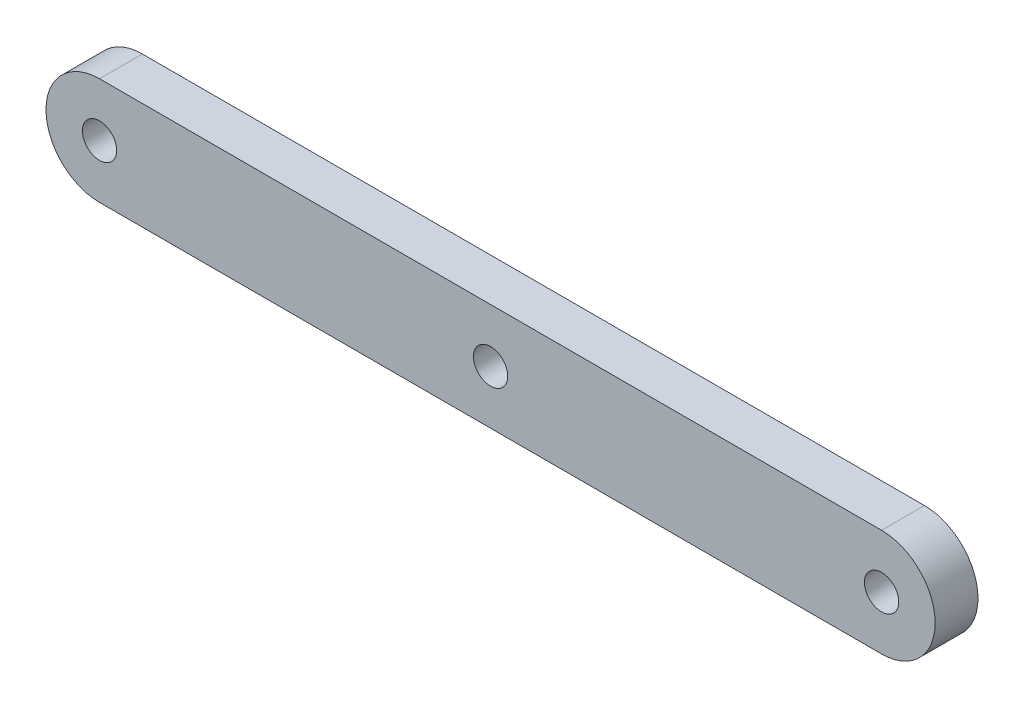
SolidWorks part; units mm, degrees
ref_plane "前视基准面" through (0, 0, 0) normal (0, 0, 1) x (1, 0, 0)
ref_plane "上视基准面" through (0, 0, 0) normal (0, 1, 0) x (1, 0, 0)
ref_plane "右视基准面" through (0, 0, 0) normal (1, 0, 0) x (0, 0, -1)
other "Configuration Table"
sketch "草图2" plane through (0, 0, 0) normal (0, 0, 1) x (1, 0, 0)
  line L0 (-43.2134, 33.7207) -> (-43.2134, 23.7207) construction
  line L1 (-79.7134, 33.7207) -> (-6.7134, 33.7207)
  line L3 (-79.7134, 23.7207) -> (-6.7134, 23.7207)
  line L6 (-37.9142, 23.7207) -> (-6.7134, 33.7207) construction
  arc A0 (-79.7134, 33.7207) -> (-79.7134, 23.7207) centre (-79.7134, 28.7207) ccw
  arc A1 (-6.7134, 33.7207) -> (-6.7134, 23.7207) centre (-6.7134, 28.7207) cw
  circle A2 centre (-79.7134, 28.7207) radius 1.6
  circle A3 centre (-6.7134, 28.7207) radius 1.6
  circle A4 centre (-43.2134, 28.7207) radius 1.6
  point P0 (-43.2134, 22.0223)
  point P12 (-43.2134, 28.7207)
  dimension "D2" = 5
  dimension "D3" = 3.2
  dimension "D4" = 3.2
  dimension "D5" = 3.2
  dimension "D1" = 73
extrude "凸台-拉伸2" add sketch "草图2" along normal blind 4
ref_plane "基准面1" through (-6.7134, 33.7207, 4) normal (-1, 0, 0) x (0, 0, 1)
